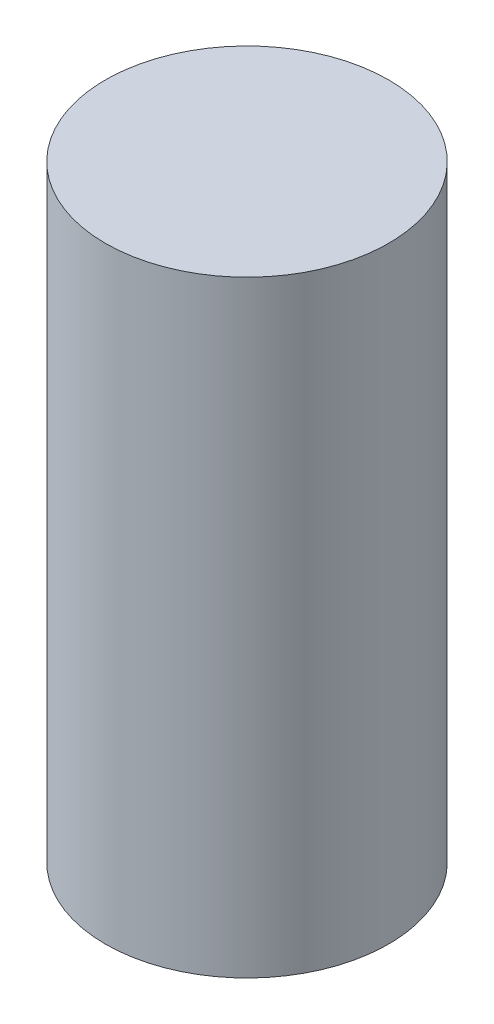
SolidWorks part; units mm, degrees
ref_plane "Front Plane" through (0, 0, 0) normal (0, 0, 1) x (1, 0, 0)
ref_plane "Top Plane" through (0, 0, 0) normal (0, 1, 0) x (1, 0, 0)
ref_plane "Right Plane" through (0, 0, 0) normal (1, 0, 0) x (0, 0, -1)
sketch "Sketch1" plane through (0, 0, 0) normal (0, 1, 0) x (1, 0, 0)
  circle A0 centre (0, 0) radius 70
  dimension "D1" = 140
extrude "Boss-Extrude1" add sketch "Sketch1" along normal blind 300 contours A0
